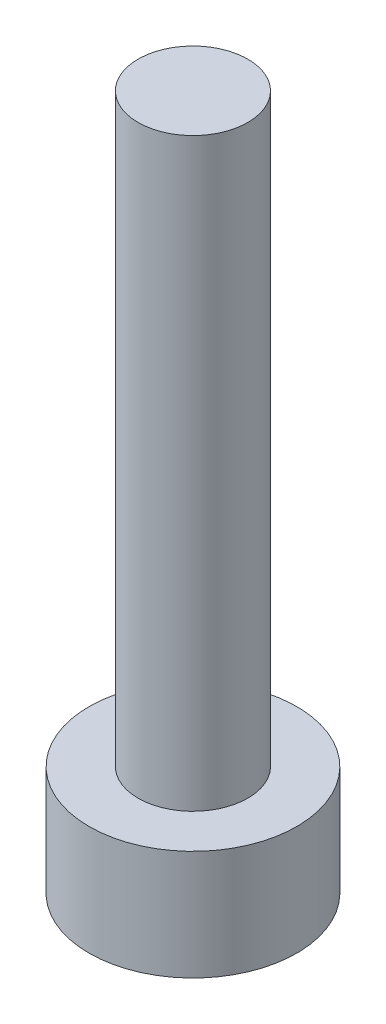
SolidWorks part; units mm, degrees
ref_plane "Front Plane" through (0, 0, 0) normal (0, 0, 1) x (1, 0, 0)
ref_plane "Top Plane" through (0, 0, 0) normal (0, 1, 0) x (1, 0, 0)
ref_plane "Right Plane" through (0, 0, 0) normal (1, 0, 0) x (0, 0, -1)
sketch "Sketch1" plane through (0, 0, 0) normal (0, 1, 0) x (1, 0, 0)
  circle A0 centre (0, 0) radius 2.84
  dimension "D1" = 5.68
extrude "Boss-Extrude1" add sketch "Sketch1" along normal blind 3
sketch "Sketch2" plane through (0, 3, 0) normal (0, 1, 0) x (1, 0, 0)
  circle A0 centre (0, 0) radius 1.5
  dimension "D1" = 3
extrude "Boss-Extrude2" add sketch "Sketch2" along normal blind 16
sketch "Sketch3" plane through (0, 0, 0) normal (0, -1, 0) x (1, 0, 0)
  line L1 (0.7448, 1.29) -> (-0.7448, 1.29)
  line L2 (-0.7448, 1.29) -> (-1.4896, 0)
  line L3 (-1.4896, 0) -> (-0.7448, -1.29)
  line L4 (-0.7448, -1.29) -> (0.7448, -1.29)
  line L5 (0.7448, -1.29) -> (1.4896, 0)
  line L6 (1.4896, 0) -> (0.7448, 1.29)
  circle A0 centre (0, 0) radius 1.29 construction
  dimension "D1" = 2.58
extrude "Cut-Extrude1" cut sketch "Sketch3" against normal blind 1.3
